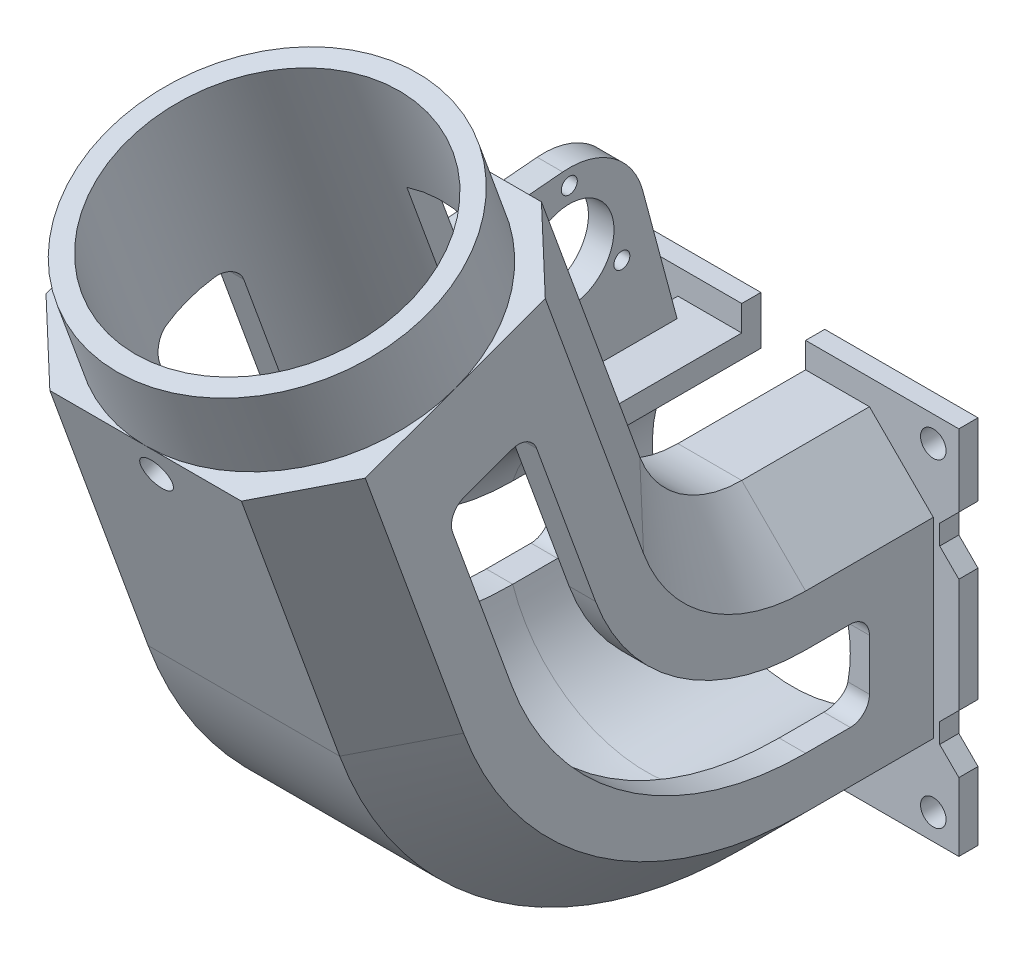
SolidWorks part; units mm, degrees
material "ABS"
ref_plane "前视基准面" through (0, 0, 0) normal (0, 0, 1) x (1, 0, 0)
ref_plane "上视基准面" through (0, 0, 0) normal (0, 1, 0) x (1, 0, 0)
ref_plane "右视基准面" through (0, 0, 0) normal (1, 0, 0) x (0, 0, -1)
sketch "草图1" plane through (0, 0, 0) normal (0, 0, 1) x (1, 0, 0)
  line L1 (-29, 58) -> (29, 58)
  line L2 (-29, 58) -> (-29, 0)
  line L3 (-29, 0) -> (29, 0)
  line L4 (29, 58) -> (29, 0)
  circle A0 centre (0, 29) radius 22
  circle A1 centre (-25, 54) radius 2
  circle A2 centre (25, 54) radius 2
  circle A3 centre (25, 4) radius 2
  circle A4 centre (-25, 4) radius 2
extrude "凸台-拉伸1" add sketch "草图1" along normal blind 3
sketch "草图2" plane through (0, 0, 3) normal (0, 0, 1) x (1, 0, 0)
  line L0 (-25, 44) -> (-15, 54)
  line L1 (-15, 4) -> (15, 4)
  line L2 (-25, 14) -> (-25, 44)
  line L3 (-15, 54) -> (15, 54)
  line L4 (25, 14) -> (25, 44)
  line L5 (-25, 4) -> (25, 54) construction
  line L6 (-25, 54) -> (25, 4) construction
  line L7 (15, 54) -> (25, 44)
  line L8 (15, 4) -> (25, 14)
  line L9 (-25, 14) -> (-15, 4)
  circle A0 centre (0, 29) radius 22
extrude "凸台-拉伸2" add sketch "草图2" along normal blind 20
sketch "草图3" plane through (0, 0, 0) normal (1, 0, 0) x (0, 0, -1)
  line L0 (-23, 71) -> (-23, 29) construction
  line L3 (-23, 71) -> (-62.4671, 56.6352) construction
  arc A0 (-62.4671, 56.6352) -> (-23, 29) centre (-23, 71) ccw
  dimension "D1" = 84
  dimension "D3" = 70
sketch "草图4" plane through (0, 0, 23) normal (0, 0, 1) x (1, 0, 0)
  line L8 (-25, 44) -> (-25, 14)
  line L9 (-25, 14) -> (-15, 4)
  line L10 (-15, 4) -> (15, 4)
  line L11 (15, 4) -> (25, 14)
  line L12 (25, 14) -> (25, 44)
  line L13 (25, 44) -> (15, 54)
  line L14 (15, 54) -> (-15, 54)
  line L15 (-15, 54) -> (-25, 44)
  line L16 (-25, 44) -> (-25, 14)
  line L17 (-25, 14) -> (-15, 4)
  line L18 (-15, 4) -> (15, 4)
  line L19 (15, 4) -> (25, 14)
  line L20 (25, 14) -> (25, 44)
  line L21 (25, 44) -> (15, 54)
  line L22 (15, 54) -> (-15, 54)
  line L23 (-15, 54) -> (-25, 44)
  circle A1 centre (0, 29) radius 22
  dimension "D1" = 0
sweep "扫描1" add profiles "草图4" path "草图3"
sketch "草图5" plane through (0, 70.0866, 25.5094) normal (0, 0.9397, 0.342) x (1, 0, 0)
  line L8 (-15, -14.3295) -> (-25, -24.3295)
  line L9 (-25, -24.3295) -> (-25, -54.3295)
  line L10 (-25, -54.3295) -> (-15, -64.3295)
  line L11 (-15, -64.3295) -> (15, -64.3295)
  line L12 (15, -64.3295) -> (25, -54.3295)
  line L13 (25, -54.3295) -> (25, -24.3295)
  line L14 (25, -24.3295) -> (15, -14.3295)
  line L15 (15, -14.3295) -> (-15, -14.3295)
  line L16 (-15, -14.3295) -> (-25, -24.3295)
  line L17 (-25, -24.3295) -> (-25, -54.3295)
  line L18 (-25, -54.3295) -> (-15, -64.3295)
  line L19 (-15, -64.3295) -> (15, -64.3295)
  line L20 (15, -64.3295) -> (25, -54.3295)
  line L21 (25, -54.3295) -> (25, -24.3295)
  line L22 (25, -24.3295) -> (15, -14.3295)
  line L23 (15, -14.3295) -> (-15, -14.3295)
  circle A0 centre (0, -39.3295) radius 22
  dimension "D1" = 0
extrude "凸台-拉伸3" add sketch "草图5" along normal blind 45
ref_plane "基准面1" through (0, 0, 23) normal (0, 0, 1) x (1, 0, 0)
ref_plane "基准面2" through (0, 70.0866, 25.5094) normal (0, -0.9397, -0.342) x (-1, 0, 0)
sketch "草图6" plane through (0, 0, 0) normal (1, 0, 0) x (0, 0, -1)
  circle A0 centre (-23, 71) radius 43.5
  dimension "D1" = 87
extrude "切除-拉伸1" cut sketch "草图6" against normal blind 5 and the other way blind 5
ref_plane "基准面3" through (0, -1.299, 0.75) normal (0, 0.866, -0.5) x (1, 0, 0)
ref_plane "基准面4" through (0, 33.342, -19.25) normal (0, 0.866, -0.5) x (1, 0, 0)
sketch "草图11" plane through (0, 112.3728, 40.9004) normal (0, 0.9397, 0.342) x (1, 0, 0)
  circle A0 centre (0, -39.3295) radius 22
  circle A1 centre (0, -39.3295) radius 25
  dimension "D1" = 50
extrude "凸台-拉伸7" add sketch "草图11" along normal blind 3
sketch "草图12" plane through (0, 115.1919, 41.9264) normal (0, 0.9397, 0.342) x (1, 0, 0)
  circle A0 centre (0, -39.3295) radius 22
  circle A1 centre (0, -39.3295) radius 25
  dimension "D1" = 50
extrude "凸台-拉伸8" add sketch "草图12" along normal blind 10
ref_plane "Plane1" through (-16, 0, 0) normal (1, 0, 0) x (0, 0, -1)
sketch "Sketch2" plane through (-16, 0, 0) normal (1, 0, 0) x (0, 0, -1)
  line L0 (-24.0372, 82.8547) -> (-46.2973, 80.9072)
  line L1 (-46.2973, 80.9072) -> (-37.4649, 56.6403)
  line L2 (-37.4649, 56.6403) -> (-28.1438, 52.6836)
  line L3 (-28.1438, 52.6836) -> (-5.7723, 52.6836)
  line L4 (-5.7723, 52.6836) -> (-11.5055, 74.0799)
  line L5 (-63.7626, 104.0516) -> (-48.3717, 61.7655) construction
  circle A0 centre (-14.7728, 66.25) radius 1.25 construction
  circle A1 centre (-31.2272, 66.25) radius 1.25 construction
  circle A2 centre (-23, 80.5) radius 1.25 construction
  circle A3 centre (-23, 71) radius 11.9 construction
  circle A4 centre (-14.7728, 66.25) radius 1.25
  circle A5 centre (-31.2272, 66.25) radius 1.25
  circle A6 centre (-23, 80.5) radius 1.25
  circle A7 centre (-23, 71) radius 11.9
  circle A8 centre (-23, 71) radius 7
  dimension "D3" = 14
  dimension "D1" = 75
  dimension "D2" = 75
extrude "Extrude1" add sketch "Sketch2" along normal blind 4 contours A7 L0 L1 L2 L3 L4 | A7 A8 A4 A5 A6
sketch "Sketch3" plane through (25, 0, 0) normal (1, 0, 0) x (0, 0, -1)
  line L0 (-68.9689, 86.194) -> (-76.4865, 83.4579)
  line L1 (-78.2795, 79.6127) -> (-69.0449, 54.241)
  line L2 (-23, 22) -> (-16, 22)
  line L3 (-13, 25) -> (-13, 33)
  line L4 (-16, 36) -> (-23, 36)
  line L5 (-55.8892, 59.0293) -> (-65.1238, 84.401)
  line L6 (-63.7626, 104.0516) -> (-48.3717, 61.7655) construction
  line L7 (-54.3657, 107.4718) -> (-77.858, 98.9213) construction
  line L8 (-23, 36) -> (-23, 22) construction
  line L9 (-55.8892, 59.0293) -> (-69.0449, 54.241) construction
  line L10 (-23, 44) -> (-23, 54) construction
  line L11 (-48.3717, 61.7655) -> (-38.9748, 65.1857) construction
  line L12 (-91.9534, 93.791) -> (-76.5625, 51.5049) construction
  arc A0 (-69.0449, 54.241) -> (-23, 22) centre (-23, 71) ccw
  arc A1 (-23, 36) -> (-55.8892, 59.0293) centre (-23, 71) cw
  arc A2 (-48.3717, 61.7655) -> (-23, 44) centre (-23, 71) ccw construction
  arc A3 (-16, 22) -> (-13, 25) centre (-16, 25) ccw
  arc A4 (-13, 33) -> (-16, 36) centre (-16, 33) ccw
  arc A5 (-68.9689, 86.194) -> (-65.1238, 84.401) centre (-67.9429, 83.3749) cw
  arc A6 (-76.4865, 83.4579) -> (-78.2795, 79.6127) centre (-75.4604, 80.6388) ccw
  dimension "D5" = 3
  dimension "D1" = 8
  dimension "D2" = 8
  dimension "D3" = 30
  dimension "D4" = 10
extrude "Cut-Extrude1" cut sketch "Sketch3" against normal blind 51
sketch "Sketch4" plane through (0, 0, 0) normal (0, 0, -1) x (-1, 0, 0)
  line L0 (-26, 16.7958) -> (-29, 19.7958) construction
  line L1 (-26, 13.7) -> (-26, 16.7958) construction
  line L2 (-29, 10.7) -> (-26, 13.7) construction
  line L3 (-29, 0) -> (-29, 58) construction
  line L4 (-26, 43.7) -> (-29, 46.7) construction
  line L5 (-29, 37.6042) -> (-26, 40.6042) construction
  line L6 (-26, 40.6042) -> (-26, 43.7) construction
  line L7 (-26, 16.7958) -> (-29, 19.7958)
  line L8 (-26, 13.7) -> (-26, 16.7958)
  line L9 (-29, 10.7) -> (-26, 13.7)
  line L10 (-29, 10.7) -> (-29, 19.7958)
  line L11 (-26, 43.7) -> (-29, 46.7)
  line L12 (-29, 37.6042) -> (-26, 40.6042)
  line L13 (-26, 40.6042) -> (-26, 43.7)
  line L14 (26, 40.6042) -> (29, 37.6042) construction
  line L15 (29, 58) -> (29, 0) construction
  line L16 (26, 43.7) -> (26, 40.6042) construction
  line L17 (29, 46.7) -> (26, 43.7) construction
  line L18 (26, 40.6042) -> (29, 37.6042)
  line L19 (29, 46.7) -> (29, 37.6042)
  line L20 (26, 43.7) -> (26, 40.6042)
  line L21 (29, 46.7) -> (26, 43.7)
  line L22 (29, 19.7958) -> (26, 16.7958) construction
  line L23 (26, 16.7958) -> (26, 13.7) construction
  line L24 (26, 13.7) -> (29, 10.7) construction
  line L25 (29, 19.7958) -> (26, 16.7958)
  line L26 (26, 16.7958) -> (26, 13.7)
  line L27 (26, 13.7) -> (29, 10.7)
  line L28 (29, 19.7958) -> (29, 10.7)
  line L29 (-29, 37.6042) -> (-29, 46.7)
extrude "Cut-Extrude2" cut sketch "Sketch4" against normal blind 3
sketch "Sketch5" plane through (0, -22.002, 60.45) normal (0, -0.342, 0.9397) x (1, 0, 0)
  line L0 (0, 114.5846) -> (0, 119.5846) construction
  circle A0 centre (0, 114.5846) radius 2.5
  dimension "D1" = 5
  dimension "D2" = 5
extrude "Cut-Extrude3" cut sketch "Sketch5" against normal blind 10
